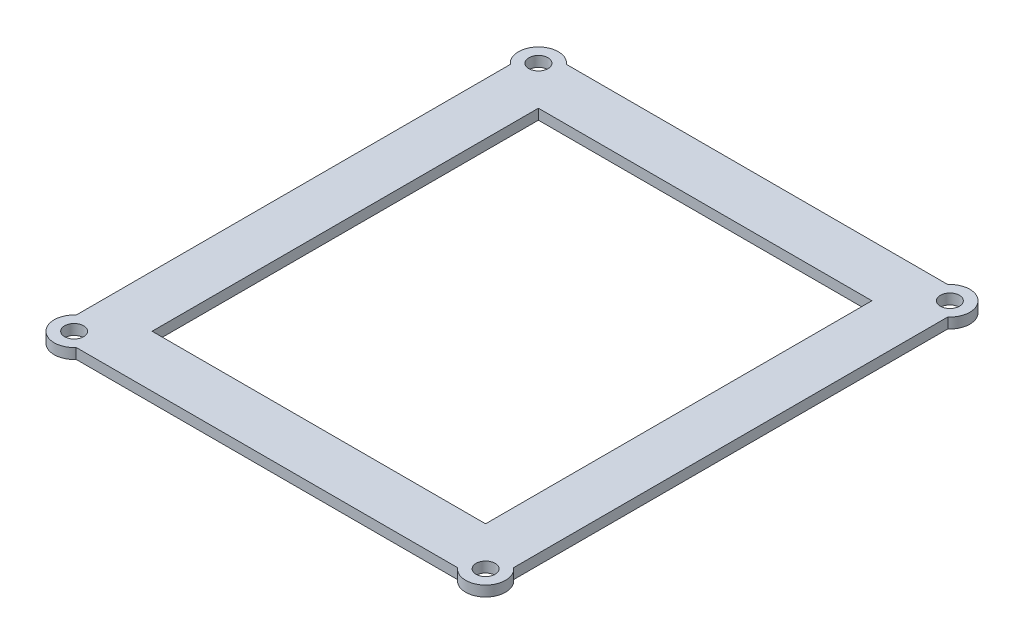
SolidWorks part; units mm, degrees
ref_plane "Front Plane" through (0, 0, 0) normal (0, 0, 1) x (1, 0, 0)
ref_plane "Top Plane" through (0, 0, 0) normal (0, 1, 0) x (1, 0, 0)
ref_plane "Right Plane" through (0, 0, 0) normal (1, 0, 0) x (0, 0, -1)
sketch "Sketch1" plane through (0, 0, 0) normal (0, 1, 0) x (1, 0, 0)
  line L1 (0, 0) -> (128.27, 0)
  line L2 (0, 0) -> (0, 143.764)
  line L3 (0, 143.764) -> (128.27, 143.764)
  line L4 (128.27, 0) -> (128.27, 143.764)
  line L5 (15.24, 15.24) -> (113.03, 15.24)
  line L6 (15.24, 15.24) -> (15.24, 128.524)
  line L7 (15.24, 128.524) -> (113.03, 128.524)
  line L8 (113.03, 15.24) -> (113.03, 128.524)
  dimension "D1" = 128.27
  dimension "D2" = 143.764
  dimension "D3" = 15.24
  dimension "D4" = 15.24
  dimension "D5" = 15.24
  dimension "D6" = 15.24
extrude "Boss-Extrude1" add sketch "Sketch1" along normal blind 3.048
sketch "Sketch2" plane through (0, 3.048, 0) normal (0, 1, 0) x (1, 0, 0)
  line L0 (128.27, 143.764) -> (0, 143.764) construction
  line L1 (0, 143.764) -> (0, 0) construction
  line L2 (0, 0) -> (128.27, 0) construction
  line L3 (128.27, 0) -> (128.27, 143.764) construction
  circle A0 centre (3.81, 139.954) radius 2.794
  circle A1 centre (124.46, 139.954) radius 2.794
  circle A2 centre (124.46, 3.81) radius 2.794
  circle A3 centre (3.81, 3.81) radius 2.794
  dimension "D1" = 5.588
  dimension "D2" = 3.81
  dimension "D4" = 3.81
  dimension "D5" = 3.81
  dimension "D6" = 3.81
  dimension "D7" = 3.81
  dimension "D8" = 3.81
  dimension "D9" = 3.81
  dimension "D3" = 3.81
extrude "Cut-Extrude1" cut sketch "Sketch2" against normal blind 3.302
sketch "Sketch4" plane through (0, 3.048, 0) normal (0, 1, 0) x (1, 0, 0)
  circle A0 centre (3.81, 139.954) radius 2.794
  circle A1 centre (3.81, 139.954) radius 5.842
  circle A2 centre (124.46, 139.954) radius 2.794
  circle A3 centre (124.46, 139.954) radius 5.842
  circle A4 centre (124.46, 3.81) radius 2.794
  circle A5 centre (124.46, 3.81) radius 5.842
  circle A6 centre (3.81, 3.81) radius 2.794
  circle A7 centre (3.81, 3.81) radius 5.842
  circle A8 centre (3.81, 3.81) radius 2.794 construction
  circle A9 centre (3.81, 139.954) radius 2.794 construction
  circle A10 centre (124.46, 139.954) radius 2.794 construction
  circle A11 centre (124.46, 3.81) radius 2.794 construction
  dimension "D1" = 3.048
  dimension "D2" = 3.048
  dimension "D3" = 3.048
  dimension "D4" = 3.048
extrude "Boss-Extrude2" add sketch "Sketch4" against normal through all
